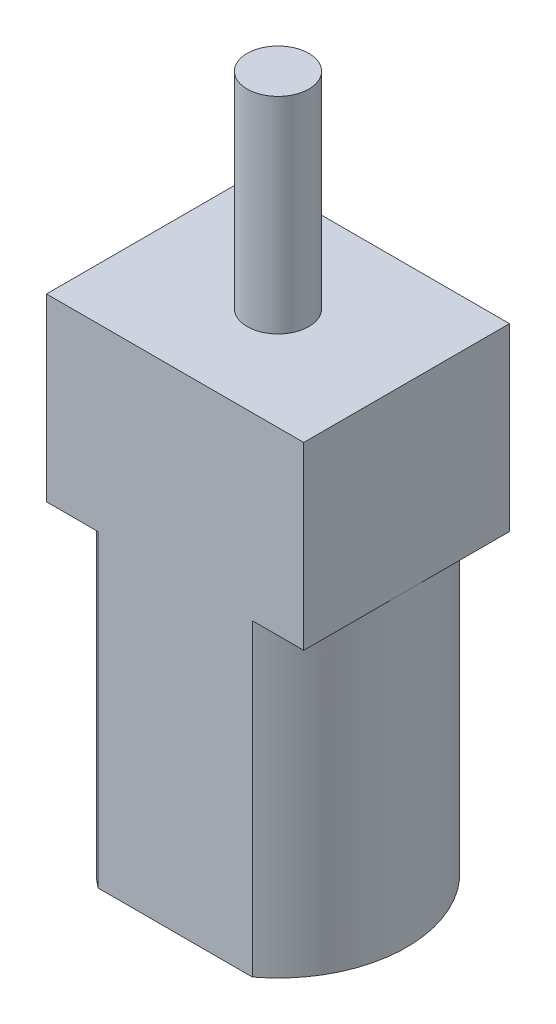
SolidWorks part; units mm, degrees
ref_plane "Front Plane" through (0, 0, 0) normal (0, 0, 1) x (1, 0, 0)
ref_plane "Top Plane" through (0, 0, 0) normal (0, 1, 0) x (1, 0, 0)
ref_plane "Right Plane" through (0, 0, 0) normal (1, 0, 0) x (0, 0, -1)
sketch "Sketch1" plane through (0, 0, 0) normal (0, 1, 0) x (1, 0, 0)
  circle A0 centre (0, 0) radius 6.35
extrude "Boss-Extrude1" add sketch "Sketch1" along normal blind 15.24
sketch "Sketch3" plane through (0, 15.24, 0) normal (0, 1, 0) x (1, 0, 0)
  line L1 (-6.35, -5.08) -> (6.35, -5.08)
  line L2 (-6.35, -5.08) -> (-6.35, 5.08)
  line L3 (-6.35, 5.08) -> (6.35, 5.08)
  line L4 (6.35, -5.08) -> (6.35, 5.08)
  line L5 (-6.35, -5.08) -> (6.35, 5.08) construction
  line L6 (-6.35, 5.08) -> (6.35, -5.08) construction
  point P0 (0, 0)
  dimension "D1" = 10.16
  dimension "D2" = 12.7
extrude "Boss-Extrude2" add sketch "Sketch3" along normal blind 8.89
sketch "Sketch4" plane through (0, 24.13, 0) normal (0, 1, 0) x (1, 0, 0)
  line L1 (-6.35, -5.08) -> (6.35, -5.08)
  line L2 (-6.35, -5.08) -> (-6.35, 5.08)
  line L3 (-6.35, 5.08) -> (6.35, 5.08)
  line L4 (6.35, -5.08) -> (6.35, 5.08)
  line L5 (-6.35, -5.08) -> (6.35, 5.08) construction
  line L6 (-6.35, 5.08) -> (6.35, -5.08) construction
  circle A0 centre (0, 0) radius 6.35
  point P0 (0, 0)
extrude "Cut-Extrude2" cut sketch "Sketch4" against normal through all contours L3 A0 | L1 A0
sketch "Sketch5" plane through (0, 24.13, 0) normal (0, 1, 0) x (1, 0, 0)
  circle A0 centre (0, 0) radius 1.524
  dimension "D1" = 3.048
extrude "Boss-Extrude3" add sketch "Sketch5" along normal blind 10.16
